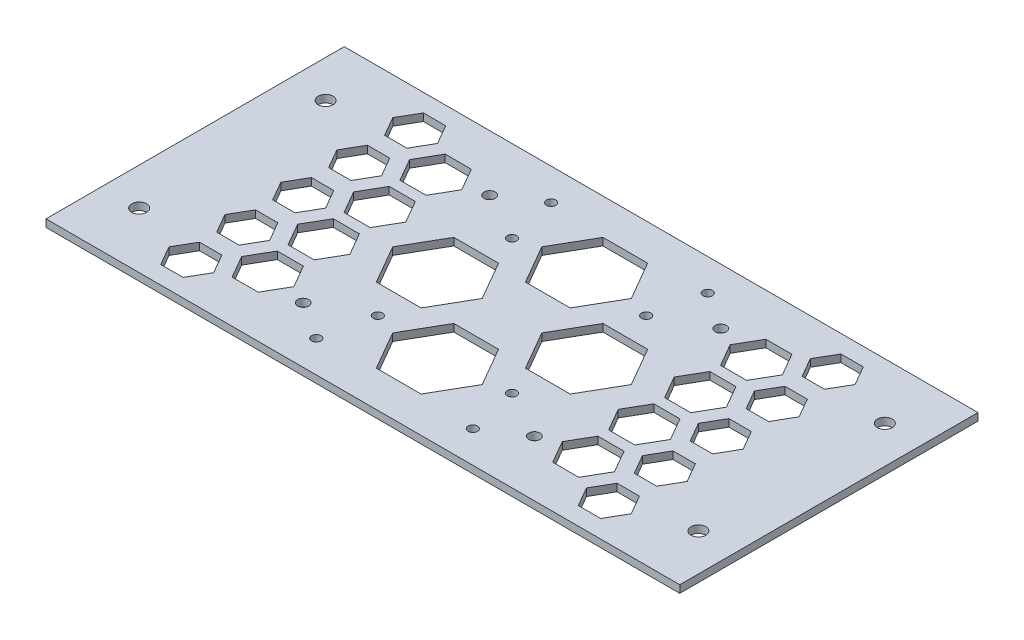
SolidWorks part; units mm, degrees
ref_plane "前视基准面" through (0, 0, 0) normal (0, 0, 1) x (1, 0, 0)
ref_plane "上视基准面" through (0, 0, 0) normal (0, 1, 0) x (1, 0, 0)
ref_plane "右视基准面" through (0, 0, 0) normal (1, 0, 0) x (0, 0, -1)
sketch "草图1" plane through (0, 0, 0) normal (0, 1, 0) x (1, 0, 0)
  line L0 (85, 80) -> (85, 0) construction
  line L1 (0, 0) -> (170, 0)
  line L2 (0, 0) -> (0, 80)
  line L3 (0, 80) -> (170, 80)
  line L4 (170, 0) -> (170, 80)
  line L5 (0, 40) -> (85, 40) construction
  line L6 (103, 58) -> (67, 58) construction
  line L7 (67, 58) -> (67, 22) construction
  line L8 (106, 71.5) -> (64, 71.5) construction
  line L9 (64, 71.5) -> (64, 8.5) construction
  line L10 (116, 65) -> (54, 65) construction
  line L11 (54, 65) -> (54, 15) construction
  circle A0 centre (10, 65) radius 2
  circle A1 centre (10, 15) radius 2
  circle A2 centre (160, 15) radius 2
  circle A3 centre (160, 65) radius 2
  circle A4 centre (67, 58) radius 1.25
  circle A5 centre (67, 22) radius 1.25
  circle A6 centre (103, 22) radius 1.25
  circle A7 centre (103, 58) radius 1.25
  circle A8 centre (64, 71.5) radius 1.25
  circle A9 centre (64, 8.5) radius 1.25
  circle A10 centre (106, 8.5) radius 1.25
  circle A11 centre (106, 71.5) radius 1.25
  circle A12 centre (54, 65) radius 1.5
  circle A13 centre (54, 15) radius 1.5
  circle A14 centre (116, 15) radius 1.5
  circle A15 centre (116, 65) radius 1.5
  dimension "D2" = 4
  dimension "D3" = 10
  dimension "D4" = 50
  dimension "D6" = 2.5
  dimension "D7" = 2.5
  dimension "D8" = 3
  dimension "D1" = 170
  dimension "D5" = 80
  dimension "D9" = 50
  dimension "D10" = 62
  dimension "D11" = 63
  dimension "D12" = 42
  dimension "D13" = 36
  dimension "D14" = 36
extrude "凸台-拉伸1" add sketch "草图1" along normal blind 2
sketch "草图3" plane through (0, 2, 0) normal (0, 1, 0) x (1, 0, 0)
  line L0 (35, 0) -> (35, 80) construction
  line L1 (26, 15.1739) -> (23, 9.9778)
  line L2 (23, 9.9778) -> (26, 4.7816)
  line L3 (26, 4.7816) -> (32, 4.7816)
  line L4 (32, 4.7816) -> (35, 9.9778)
  line L5 (35, 9.9778) -> (32, 15.1739)
  line L6 (32, 15.1739) -> (26, 15.1739)
  line L7 (0, 0) -> (170, 0) construction
  line L8 (170, 80) -> (0, 80) construction
  line L9 (85, 0) -> (85, 80) construction
  line L10 (29, 9.9778) -> (42, 17.4833) construction
  line L11 (38.5, 23.5455) -> (35, 17.4833)
  line L12 (35, 17.4833) -> (38.5, 11.4212)
  line L13 (38.5, 11.4212) -> (45.5, 11.4212)
  line L14 (45.5, 11.4212) -> (49, 17.4833)
  line L15 (49, 17.4833) -> (45.5, 23.5455)
  line L16 (45.5, 23.5455) -> (38.5, 23.5455)
  line L17 (35, 40) -> (73.3158, 40) construction
  line L18 (42, 17.4833) -> (29, 24.9889) construction
  line L19 (32, 30.185) -> (26, 30.185)
  line L20 (26, 30.185) -> (23, 24.9889)
  line L21 (23, 24.9889) -> (26, 19.7927)
  line L22 (26, 19.7927) -> (32, 19.7927)
  line L23 (32, 19.7927) -> (35, 24.9889)
  line L24 (35, 24.9889) -> (32, 30.185)
  line L25 (29, 24.9889) -> (42, 32.4944) construction
  line L26 (45.5, 38.5566) -> (38.5, 38.5566)
  line L27 (38.5, 38.5566) -> (35, 32.4944)
  line L28 (35, 32.4944) -> (38.5, 26.4323)
  line L29 (38.5, 26.4323) -> (45.5, 26.4323)
  line L30 (45.5, 26.4323) -> (49, 32.4944)
  line L31 (49, 32.4944) -> (45.5, 38.5566)
  line L32 (42, 32.4944) -> (29, 40) construction
  line L33 (32, 45.1962) -> (26, 45.1962)
  line L34 (26, 45.1962) -> (23, 40)
  line L35 (23, 40) -> (26, 34.8038)
  line L36 (26, 34.8038) -> (32, 34.8038)
  line L37 (32, 34.8038) -> (35, 40)
  line L38 (35, 40) -> (32, 45.1962)
  line L39 (49, 47.5056) -> (45.5, 41.4434)
  line L40 (45.5, 53.5677) -> (49, 47.5056)
  line L41 (38.5, 53.5677) -> (45.5, 53.5677)
  line L42 (35, 47.5056) -> (38.5, 53.5677)
  line L43 (38.5, 41.4434) -> (35, 47.5056)
  line L44 (45.5, 41.4434) -> (38.5, 41.4434)
  line L45 (45.5, 56.4545) -> (38.5, 56.4545)
  line L46 (49, 62.5167) -> (45.5, 56.4545)
  line L47 (45.5, 68.5788) -> (49, 62.5167)
  line L48 (38.5, 68.5788) -> (45.5, 68.5788)
  line L49 (35, 62.5167) -> (38.5, 68.5788)
  line L50 (38.5, 56.4545) -> (35, 62.5167)
  line L51 (35, 55.0111) -> (32, 49.815)
  line L52 (32, 60.2073) -> (35, 55.0111)
  line L53 (26, 60.2073) -> (32, 60.2073)
  line L54 (23, 55.0111) -> (26, 60.2073)
  line L55 (26, 49.815) -> (23, 55.0111)
  line L56 (32, 49.815) -> (26, 49.815)
  line L57 (32, 64.8261) -> (26, 64.8261)
  line L58 (35, 70.0222) -> (32, 64.8261)
  line L59 (32, 75.2184) -> (35, 70.0222)
  line L60 (26, 75.2184) -> (32, 75.2184)
  line L61 (23, 70.0222) -> (26, 75.2184)
  line L62 (26, 64.8261) -> (23, 70.0222)
  line L63 (128, 32.4944) -> (141, 40) construction
  line L64 (141, 24.9889) -> (128, 32.4944) construction
  line L65 (128, 17.4833) -> (141, 24.9889) construction
  line L66 (141, 9.9778) -> (128, 17.4833) construction
  line L67 (135, 0) -> (135, 80) construction
  line L68 (144, 64.8261) -> (147, 70.0222)
  line L69 (147, 70.0222) -> (144, 75.2184)
  line L70 (144, 75.2184) -> (138, 75.2184)
  line L71 (138, 75.2184) -> (135, 70.0222)
  line L72 (135, 70.0222) -> (138, 64.8261)
  line L73 (138, 64.8261) -> (144, 64.8261)
  line L74 (138, 49.815) -> (144, 49.815)
  line L75 (144, 49.815) -> (147, 55.0111)
  line L76 (147, 55.0111) -> (144, 60.2073)
  line L77 (144, 60.2073) -> (138, 60.2073)
  line L78 (138, 60.2073) -> (135, 55.0111)
  line L79 (135, 55.0111) -> (138, 49.815)
  line L80 (131.5, 56.4545) -> (135, 62.5167)
  line L81 (135, 62.5167) -> (131.5, 68.5788)
  line L82 (131.5, 68.5788) -> (124.5, 68.5788)
  line L83 (124.5, 68.5788) -> (121, 62.5167)
  line L84 (121, 62.5167) -> (124.5, 56.4545)
  line L85 (124.5, 56.4545) -> (131.5, 56.4545)
  line L86 (124.5, 41.4434) -> (131.5, 41.4434)
  line L87 (131.5, 41.4434) -> (135, 47.5056)
  line L88 (135, 47.5056) -> (131.5, 53.5677)
  line L89 (131.5, 53.5677) -> (124.5, 53.5677)
  line L90 (124.5, 53.5677) -> (121, 47.5056)
  line L91 (121, 47.5056) -> (124.5, 41.4434)
  line L92 (135, 40) -> (138, 45.1962)
  line L93 (138, 34.8038) -> (135, 40)
  line L94 (144, 34.8038) -> (138, 34.8038)
  line L95 (147, 40) -> (144, 34.8038)
  line L96 (144, 45.1962) -> (147, 40)
  line L97 (138, 45.1962) -> (144, 45.1962)
  line L98 (121, 32.4944) -> (124.5, 38.5566)
  line L99 (124.5, 26.4323) -> (121, 32.4944)
  line L100 (131.5, 26.4323) -> (124.5, 26.4323)
  line L101 (135, 32.4944) -> (131.5, 26.4323)
  line L102 (131.5, 38.5566) -> (135, 32.4944)
  line L103 (124.5, 38.5566) -> (131.5, 38.5566)
  line L104 (135, 24.9889) -> (138, 30.185)
  line L105 (138, 19.7927) -> (135, 24.9889)
  line L106 (144, 19.7927) -> (138, 19.7927)
  line L107 (147, 24.9889) -> (144, 19.7927)
  line L108 (144, 30.185) -> (147, 24.9889)
  line L109 (138, 30.185) -> (144, 30.185)
  line L110 (124.5, 23.5455) -> (131.5, 23.5455)
  line L111 (121, 17.4833) -> (124.5, 23.5455)
  line L112 (124.5, 11.4212) -> (121, 17.4833)
  line L113 (131.5, 11.4212) -> (124.5, 11.4212)
  line L114 (135, 17.4833) -> (131.5, 11.4212)
  line L115 (131.5, 23.5455) -> (135, 17.4833)
  line L116 (138, 15.1739) -> (144, 15.1739)
  line L117 (135, 9.9778) -> (138, 15.1739)
  line L118 (138, 4.7816) -> (135, 9.9778)
  line L119 (144, 4.7816) -> (138, 4.7816)
  line L120 (147, 9.9778) -> (144, 4.7816)
  line L121 (144, 15.1739) -> (147, 9.9778)
  circle A0 centre (29, 9.9778) radius 5.1962 construction
  circle A1 centre (42, 17.4833) radius 6.0622 construction
  circle A2 centre (29, 24.9889) radius 5.1962 construction
  circle A3 centre (42, 32.4944) radius 6.0622 construction
  circle A4 centre (29, 40) radius 5.1962 construction
  circle A5 centre (141, 40) radius 5.1962 construction
  circle A6 centre (128, 32.4944) radius 6.0622 construction
  circle A7 centre (141, 24.9889) radius 5.1962 construction
  circle A8 centre (128, 17.4833) radius 6.0622 construction
  circle A9 centre (141, 9.9778) radius 5.1962 construction
  dimension "D1" = 50
  dimension "D2" = 6
  dimension "D3" = 7
  dimension "D4" = 60
  dimension "D5" = 60
  dimension "D6" = 60
  dimension "D7" = 60
extrude "切除-拉伸1" cut sketch "草图3" against normal blind 50
sketch "草图4" plane through (0, 2, 0) normal (0, 1, 0) x (1, 0, 0)
  line L0 (85, 0) -> (85, 80) construction
  line L1 (77, 40) -> (71, 50.3923)
  line L2 (71, 50.3923) -> (59, 50.3923)
  line L3 (59, 50.3923) -> (53, 40)
  line L4 (53, 40) -> (59, 29.6077)
  line L5 (59, 29.6077) -> (71, 29.6077)
  line L6 (71, 29.6077) -> (77, 40)
  line L13 (0, 0) -> (170, 0) construction
  line L14 (170, 80) -> (0, 80) construction
  line L15 (65, 40) -> (85, 40) construction
  line L16 (99, 29.6077) -> (93, 40)
  line L17 (111, 29.6077) -> (99, 29.6077)
  line L18 (117, 40) -> (111, 29.6077)
  line L19 (111, 50.3923) -> (117, 40)
  line L20 (99, 50.3923) -> (111, 50.3923)
  line L21 (93, 40) -> (99, 50.3923)
  circle A0 centre (65, 40) radius 10.3923 construction
  dimension "D1" = 20
  dimension "D2" = 12
extrude "切除-拉伸2" cut sketch "草图4" against normal blind 50
sketch "草图5" plane through (0, 2, 0) normal (0, 1, 0) x (1, 0, 0)
  line L0 (0, 40) -> (170, 40) construction
  line L1 (91, 30.3923) -> (79, 30.3923)
  line L2 (79, 30.3923) -> (73, 20)
  line L3 (73, 20) -> (79, 9.6077)
  line L4 (79, 9.6077) -> (91, 9.6077)
  line L5 (91, 9.6077) -> (97, 20)
  line L6 (97, 20) -> (91, 30.3923)
  line L7 (0, 80) -> (0, 0) construction
  line L8 (170, 0) -> (170, 80) construction
  line L9 (85, 40) -> (85, 20) construction
  line L10 (97, 60) -> (91, 49.6077)
  line L11 (91, 70.3923) -> (97, 60)
  line L12 (79, 70.3923) -> (91, 70.3923)
  line L13 (73, 60) -> (79, 70.3923)
  line L14 (79, 49.6077) -> (73, 60)
  line L15 (91, 49.6077) -> (79, 49.6077)
  circle A0 centre (85, 20) radius 10.3923 construction
  dimension "D1" = 20
  dimension "D2" = 12
extrude "切除-拉伸3" cut sketch "草图5" against normal blind 50
